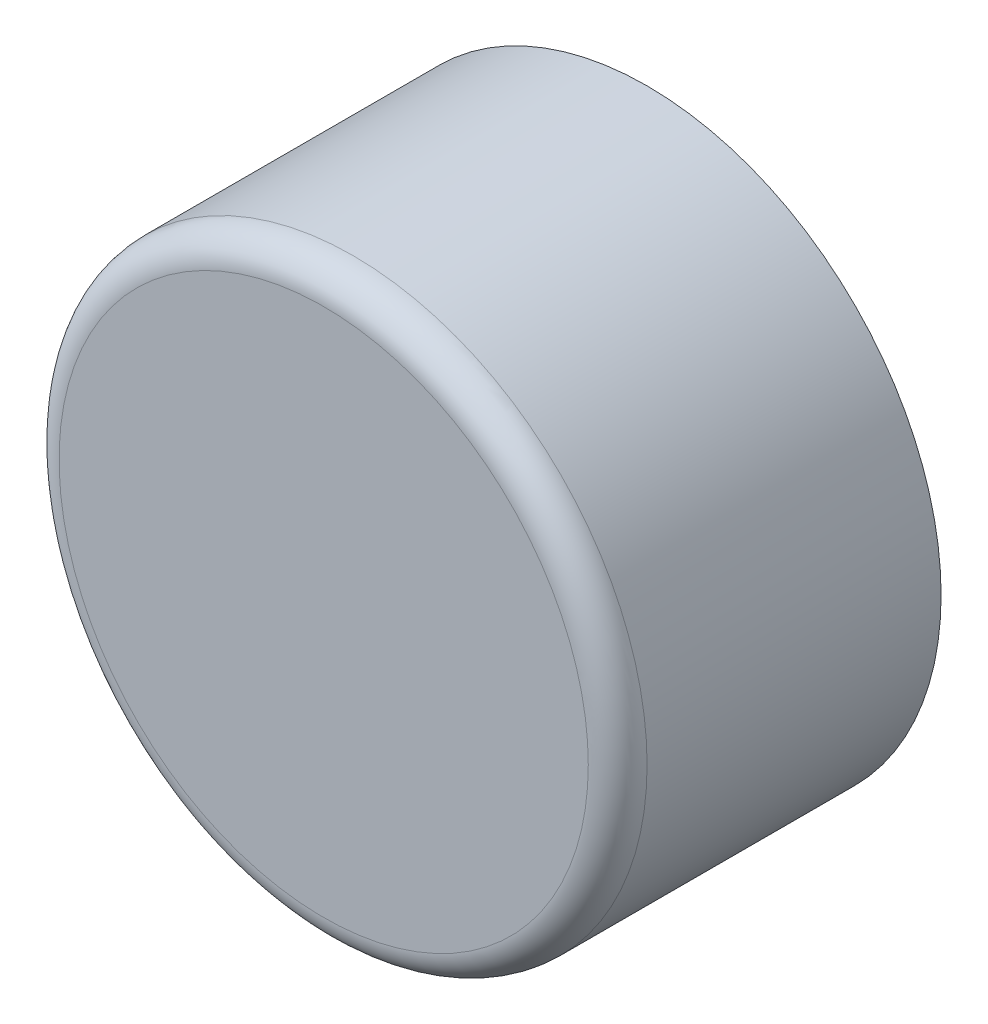
SolidWorks part; units mm, degrees
ref_plane "Front Plane" through (0, 0, 0) normal (0, 0, 1) x (1, 0, 0)
ref_plane "Top Plane" through (0, 0, 0) normal (0, 1, 0) x (1, 0, 0)
ref_plane "Right Plane" through (0, 0, 0) normal (1, 0, 0) x (0, 0, -1)
sketch "Sketch1" plane through (0, 0, 0) normal (0, 0, 1) x (1, 0, 0)
  circle A0 centre (0, 0) radius 17
  circle A1 centre (0, 0) radius 20
  dimension "D1" = 34
  dimension "D2" = 3
extrude "Boss-Extrude1" add sketch "Sketch1" along normal blind 20
sketch "Sketch2" plane through (0, 0, 20) normal (0, 0, 1) x (1, 0, 0)
  circle A0 centre (0, 0) radius 20
extrude "Boss-Extrude2" add sketch "Sketch2" along normal blind 2
fillet "Fillet1" radius 2 1 edges at (20, 0, 22)
